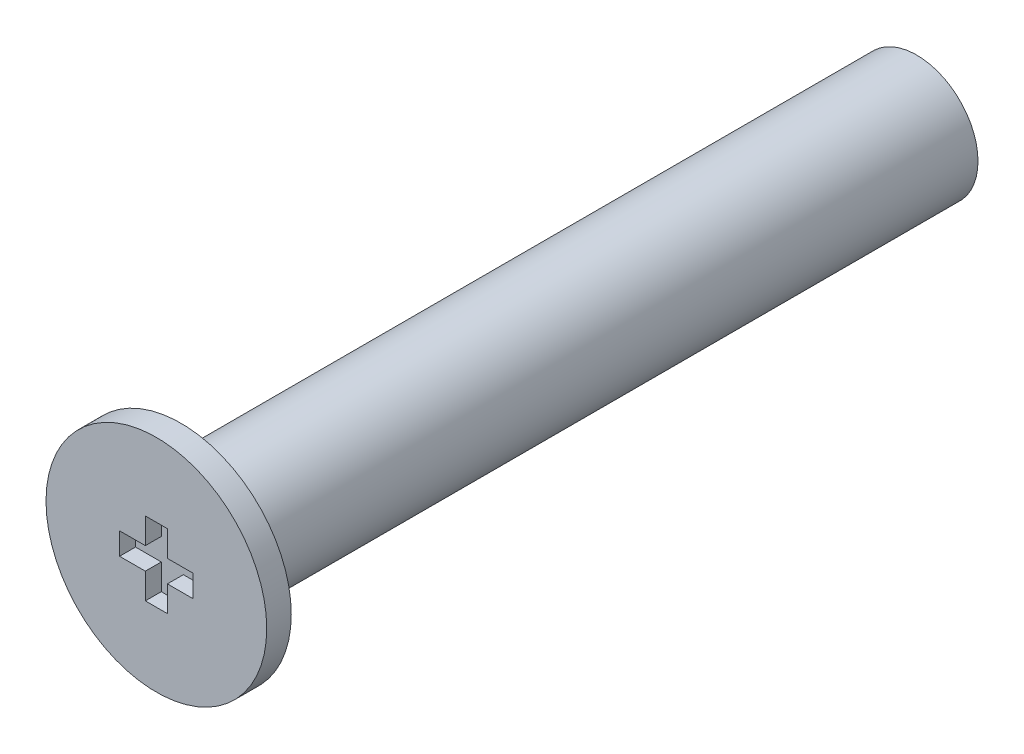
SolidWorks part; units mm, degrees
ref_plane "前视基准面" through (0, 0, 0) normal (0, 0, 1) x (1, 0, 0)
ref_plane "上视基准面" through (0, 0, 0) normal (0, 1, 0) x (1, 0, 0)
ref_plane "右视基准面" through (0, 0, 0) normal (1, 0, 0) x (0, 0, -1)
other "Configuration Table"
sketch "草图1" plane through (0, 0, 0) normal (0, 0, 1) x (1, 0, 0)
  circle A0 centre (0, 0) radius 2.5
extrude "标准杆径_头下长度" add sketch "草图1" against normal blind 30
sketch "草图2" plane through (0, 0, 0) normal (0, 0, 1) x (1, 0, 0)
  circle A0 centre (0, 0) radius 4.25
sketch "草图4" plane through (0, 0, 0) normal (0, 1, 0) x (1, 0, 0)
  line L0 (0, 0) -> (5.9, 0)
  line L1 (5.9, 0) -> (5.9, -0.3477)
  line L2 (0, -3.1) -> (0, 0)
  line L3 (0, 2) -> (0, -5.1) construction
  arc A0 (5.9, -0.3477) -> (0, -3.1) centre (0, 4.6) cw
sketch "草图5" plane through (0, 0, 0) normal (0, 0, 1) x (1, 0, 0)
  line L0 (-0.5, -2.5) -> (0.5, -2.5)
  line L1 (0.5, -2.5) -> (0.5, -0.5)
  line L2 (0.5, -0.5) -> (2.5, -0.5)
  line L3 (2.5, -0.5) -> (2.5, 0.5)
  line L4 (2.5, 0.5) -> (0.5, 0.5)
  line L5 (0.5, 0.5) -> (0.5, 2.5)
  line L6 (0.5, 2.5) -> (-0.5, 2.5)
  line L7 (-0.5, 2.5) -> (-0.5, 0.5)
  line L8 (-0.5, 0.5) -> (-2.5, 0.5)
  line L9 (-2.5, 0.5) -> (-2.5, -0.5)
  line L10 (-2.5, -0.5) -> (-0.5, -0.5)
  line L11 (-0.5, -0.5) -> (-0.5, -2.5)
sketch "草图6" plane through (0, 0, 0) normal (0, 1, 0) x (1, 0, 0)
  line L0 (0, 0) -> (4.5, 0)
  line L1 (4.5, 0) -> (4.5, -1)
  line L2 (4.5, -1) -> (0, -1)
  line L3 (0, -1) -> (0, 0)
  line L4 (0, 2) -> (0, -3) construction
revolve "已确认_十字槽超薄头" add sketch "草图6" angle 360 about L4
sketch "草图7" plane through (0, 0, 0) normal (0, 0, 1) x (1, 0, 0)
  line L0 (-0.45, -1.5) -> (0.45, -1.5)
  line L1 (0.45, -1.5) -> (0.45, -0.45)
  line L2 (0.45, -0.45) -> (1.5, -0.45)
  line L3 (1.5, -0.45) -> (1.5, 0.45)
  line L4 (1.5, 0.45) -> (0.45, 0.45)
  line L5 (0.45, 0.45) -> (0.45, 1.5)
  line L6 (0.45, 1.5) -> (-0.45, 1.5)
  line L7 (-0.45, 1.5) -> (-0.45, 0.45)
  line L8 (-0.45, 0.45) -> (-1.5, 0.45)
  line L9 (-1.5, 0.45) -> (-1.5, -0.45)
  line L10 (-1.5, -0.45) -> (-0.45, -0.45)
  line L11 (-0.45, -0.45) -> (-0.45, -1.5)
extrude "十字槽_PH2_简化" cut sketch "草图7" against normal blind 0.66 from offset 1.01
